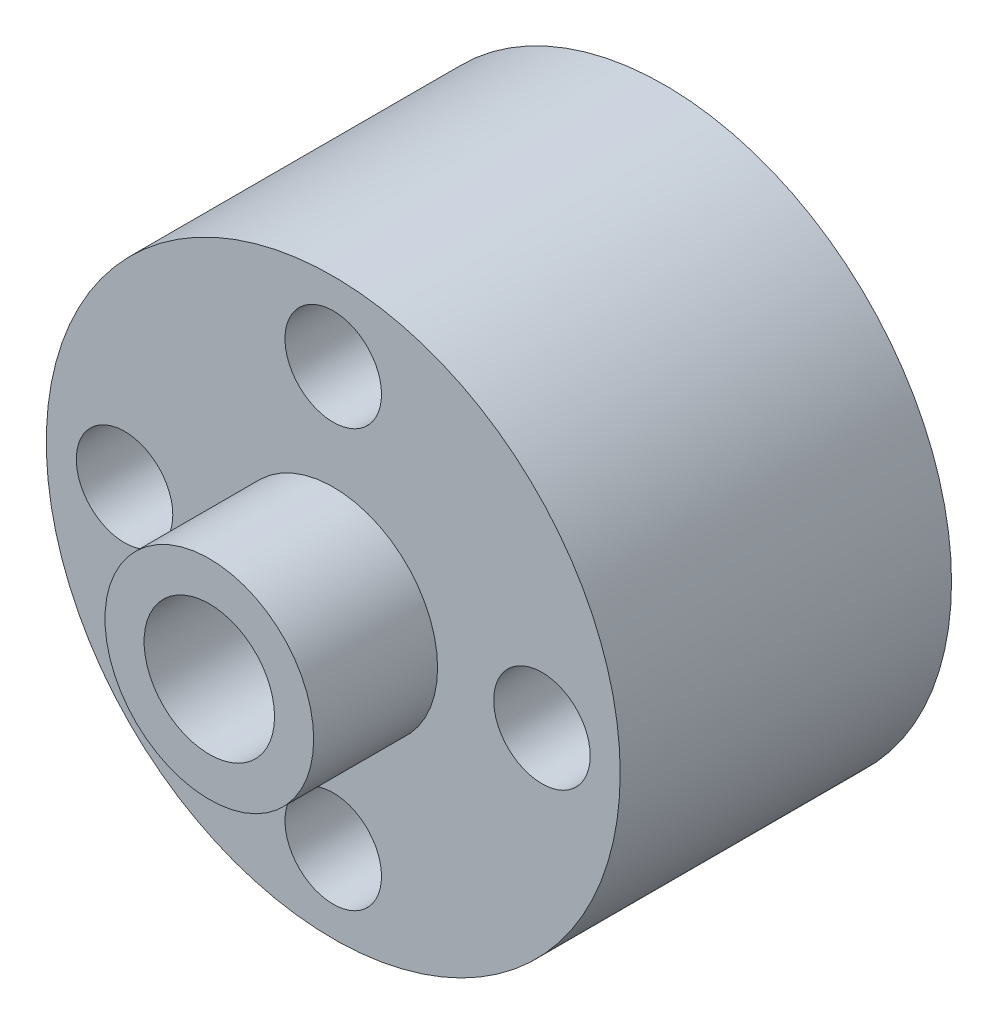
SolidWorks part; units mm, degrees
other "Defeature"
material "6061 Alloy"
ref_plane "Front Plane" through (0, 0, 0) normal (0, 0, 1) x (1, 0, 0)
ref_plane "Top Plane" through (0, 0, 0) normal (0, 1, 0) x (1, 0, 0)
ref_plane "Right Plane" through (0, 0, 0) normal (1, 0, 0) x (0, 0, -1)
sketch "Sketch1" plane through (0, 0, 0) normal (0, 0, 1) x (1, 0, 0)
  circle A0 centre (0, 0) radius 11
  dimension "D1" = 22
extrude "Boss-Extrude1" add sketch "Sketch1" against normal mid plane 12.7
sketch "Sketch3" plane through (0, 0, 6.35) normal (0, 0, 1) x (1, 0, 0)
  circle A0 centre (0, 0) radius 8 construction
  circle A1 centre (8, 0) radius 1.85
  circle A2 centre (-8, 0) radius 1.85
  circle A3 centre (0, -8) radius 1.85
  circle A4 centre (0, 8) radius 1.85
  dimension "D1" = 3.7
  dimension "D2" = 16
extrude "Cut-Extrude1" cut sketch "Sketch3" against normal through all
sketch "Sketch6" plane through (0, 0, 6.35) normal (0, 0, 1) x (1, 0, 0)
  circle A0 centre (0, 0) radius 4
  dimension "D1" = 8
extrude "Boss-Extrude2" add sketch "Sketch6" along normal blind 4.75
mirror "Mirror1" about plane through (0, 0, 0) normal (0, 0, 1) of "Boss-Extrude2"
sketch "Sketch8" plane through (0, 0, 11.1) normal (0, 0, 1) x (1, 0, 0)
  circle A0 centre (0, 0) radius 2.5
  dimension "D1" = 5
extrude "Cut-Extrude2" cut sketch "Sketch8" against normal through all
